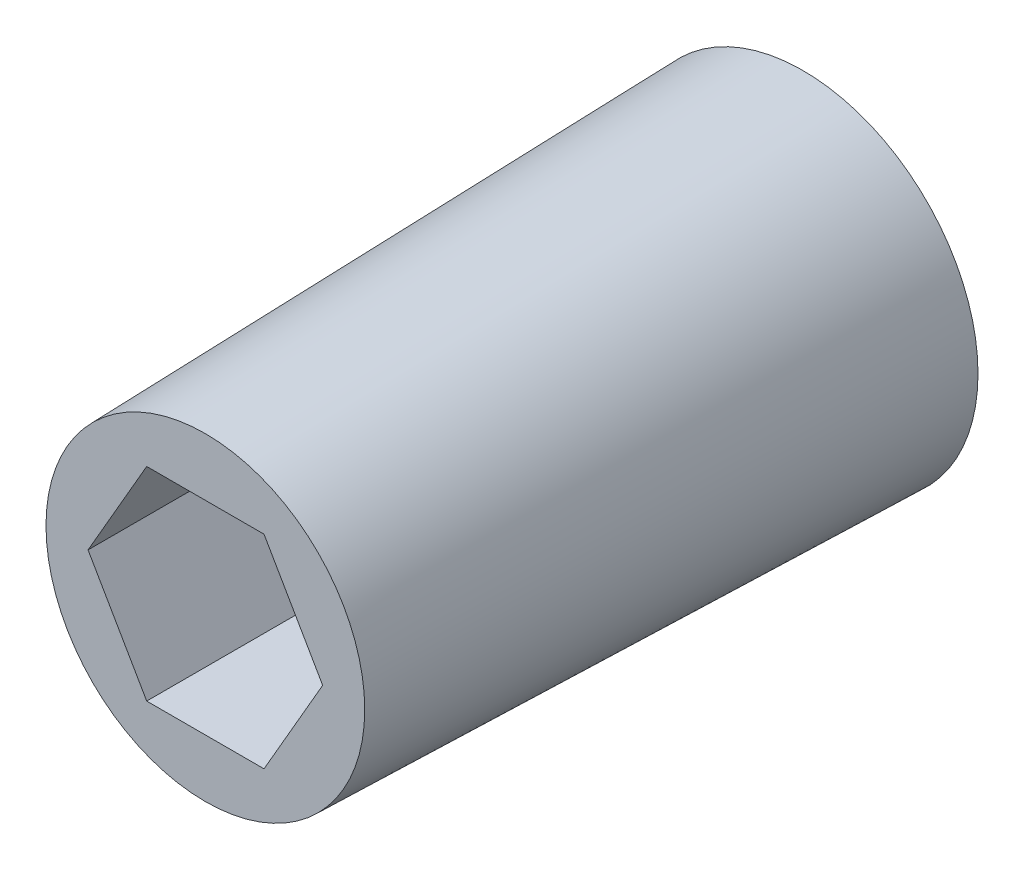
SolidWorks part; units mm, degrees
ref_plane "Front Plane" through (0, 0, 0) normal (0, 0, 1) x (1, 0, 0)
ref_plane "Top Plane" through (0, 0, 0) normal (0, 1, 0) x (1, 0, 0)
ref_plane "Right Plane" through (0, 0, 0) normal (1, 0, 0) x (0, 0, -1)
sketch "Sketch1" plane through (0, 0, 0) normal (0, 1, 0) x (1, 0, 0)
  line L0 (4.3928, 7.5) -> (0, 7.5)
  line L1 (0, 7.5) -> (0, -7.5)
  line L2 (0, -7.5) -> (4, -7.5)
  line L3 (4, -7.5) -> (4.3928, 7.5)
  line L4 (0, 7.5) -> (0, -7.5) construction
revolve "Revolve1" add sketch "Sketch1" angle 360 about L4
sketch "Sketch2" plane through (0, 0, -7.5) normal (0, 0, -1) x (-1, 0, 0)
  line L0 (-2.9445, 0) -> (-1.4722, -2.55)
  line L1 (-1.4722, -2.55) -> (1.4722, -2.55)
  line L2 (1.4722, -2.55) -> (2.9445, 0)
  line L3 (2.9445, 0) -> (1.4722, 2.55)
  line L4 (1.4722, 2.55) -> (-1.4722, 2.55)
  line L5 (-1.4722, 2.55) -> (-2.9445, 0)
extrude "Cut-Extrude1" cut sketch "Sketch2" against normal through all
